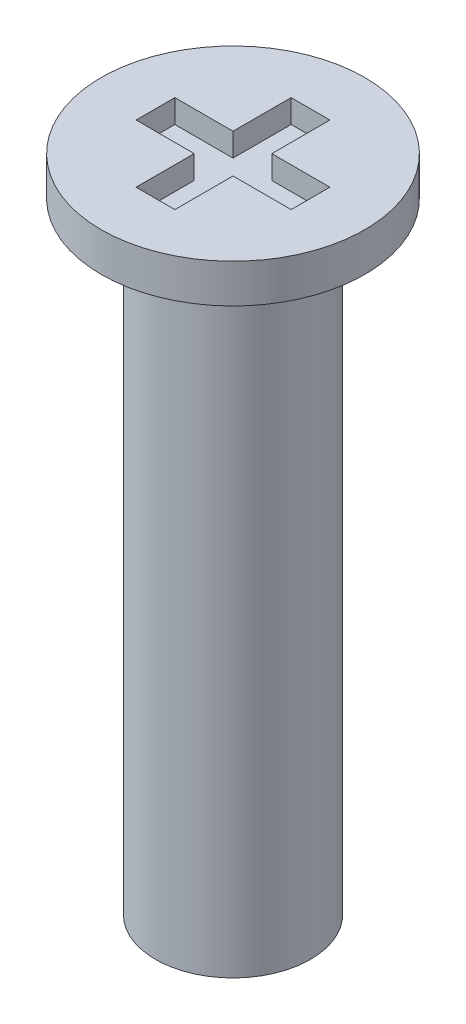
SolidWorks part; units mm, degrees
material "S45C"
ref_plane "正面" through (0, 0, 0) normal (0, 0, 1) x (1, 0, 0)
ref_plane "平面" through (0, 0, 0) normal (0, 1, 0) x (1, 0, 0)
ref_plane "右側面" through (0, 0, 0) normal (1, 0, 0) x (0, 0, -1)
sketch "ｽｹｯﾁ1" plane through (0, 0, 0) normal (0, 0, 1) x (1, 0, 0)
  line L0 (0, 0) -> (1.7, 0)
  line L1 (1.7, 0) -> (1.7, -0.5)
  line L2 (1.7, -0.5) -> (1, -0.5)
  line L3 (1, -0.5) -> (1, -8.5)
  line L4 (1, -8.5) -> (0, -8.5)
  line L5 (0, -8.5) -> (0, 0)
  dimension "D1" = 1.7
  dimension "D2" = 0.5
  dimension "D3" = 1
  dimension "D4" = 8
revolve "回転1" add sketch "ｽｹｯﾁ1" angle 360 about L5
sketch "ｽｹｯﾁ2" plane through (0, 0, 0) normal (0, 1, 0) x (1, 0, 0)
  line L1 (-0.25, 0) -> (0.25, 0)
  line L2 (-0.25, 0) -> (-0.25, 1)
  line L3 (-0.25, 1) -> (0.25, 1)
  line L4 (0.25, 0) -> (0.25, 1)
  line L5 (-0.25, 0) -> (0.25, 1) construction
  line L6 (-0.25, 1) -> (0.25, 0) construction
  point P4 (0, 0.5)
  dimension "D1" = 0
  dimension "D2" = 0.5
  dimension "D3" = 1
  dimension "D4" = 0
extrude "ｶｯﾄ - 押し出し1" cut sketch "ｽｹｯﾁ2" against normal blind 0.3
pattern_circular "円形ﾊﾟﾀｰﾝ1" count 4 over 360 about axis through (0, 0, 0) along (0, 1, 0) of "ｶｯﾄ - 押し出し1"
